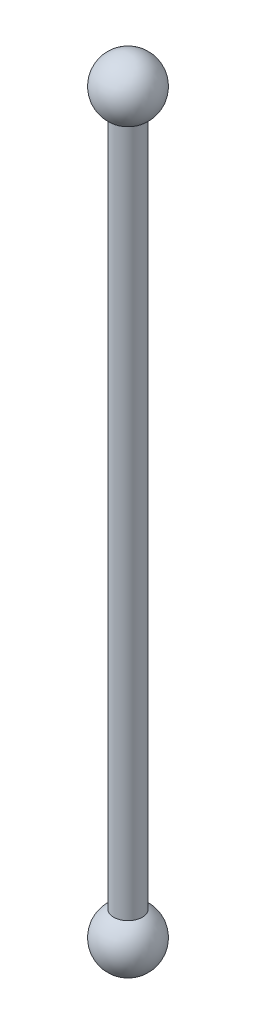
SolidWorks part; units mm, degrees
ref_plane "Front" through (0, 0, 0) normal (0, 0, 1) x (1, 0, 0)
ref_plane "Top" through (0, 0, 0) normal (0, 1, 0) x (1, 0, 0)
ref_plane "Right" through (0, 0, 0) normal (1, 0, 0) x (0, 0, -1)
sketch "Sketch1" plane through (0, 0, 0) normal (0, 0, 1) x (1, 0, 0)
  line L0 (0, -9.3301) -> (0, 60)
  line L2 (2.5, 60) -> (2.5, 0)
  line L3 (-3.3711, -9.3301) -> (9.3164, -9.3301) construction
  line L4 (2.5, 60) -> (0, 60)
  arc A0 (0, -9.3301) -> (2.5, 0) centre (0, -4.3301) ccw
  dimension "D2" = 5
  dimension "D1" = 2.5
  dimension "D3" = 60
revolve "Revolve1" add sketch "Sketch1" angle 360 about L0
mirror "Mirror1" about plane through (2.5, 60, 0) normal (0, 1, 0) of "Revolve1"
